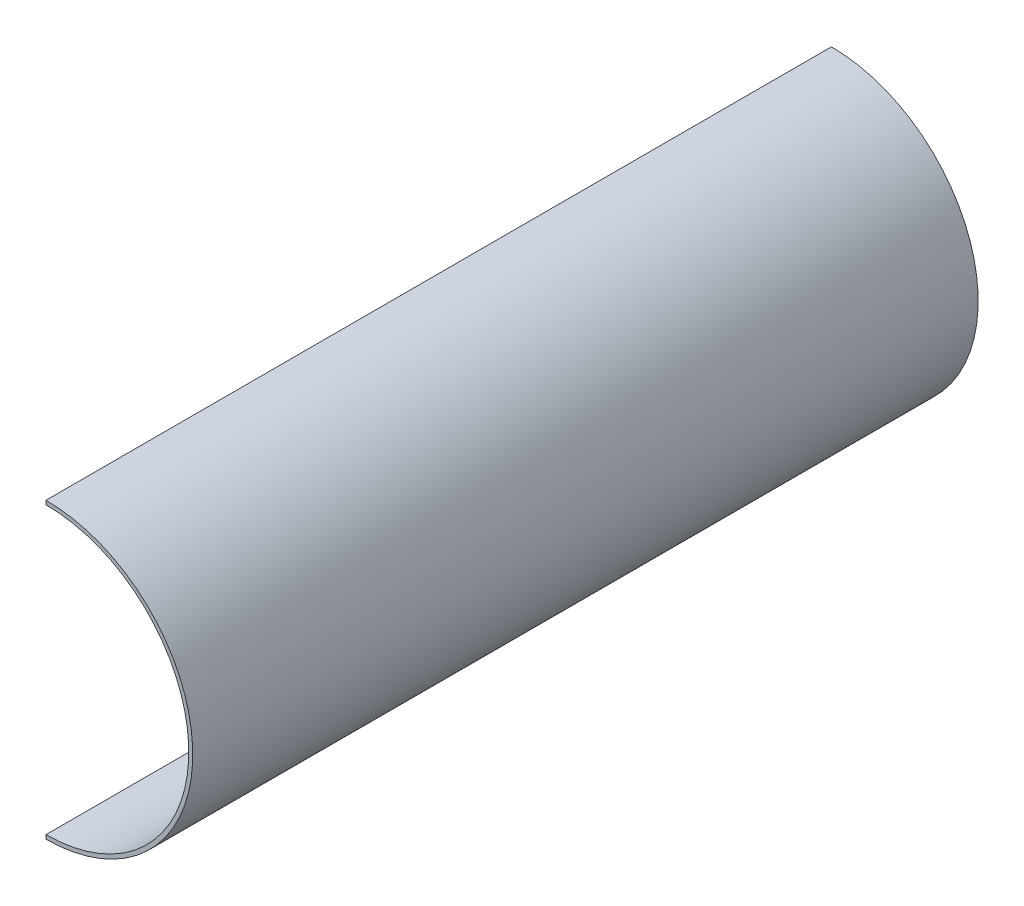
SolidWorks part; units mm, degrees
ref_plane "Front Plane" through (0, 0, 0) normal (0, 0, 1) x (1, 0, 0)
ref_plane "Top Plane" through (0, 0, 0) normal (0, 1, 0) x (1, 0, 0)
ref_plane "Right Plane" through (0, 0, 0) normal (1, 0, 0) x (0, 0, -1)
sketch "Sketch1" plane through (0, 0, 0) normal (0, 0, 1) x (1, 0, 0)
  circle A0 centre (0, 0) radius 18.5
  dimension "D1" = 37
extrude "Boss-Extrude1" add sketch "Sketch1" along normal blind 99
sketch "Sketch2" plane through (0, 0, 99) normal (0, 0, 1) x (1, 0, 0)
  line L0 (0, 18.5) -> (0, 18)
  line L1 (0, -18) -> (0, -18.5)
  arc A0 (0, 18.5) -> (0, -18.5) centre (0, 0) ccw
  arc A1 (0, -18) -> (0, 18) centre (0, 0) ccw
  dimension "D1" = 36
extrude "Cut-Extrude1" cut sketch "Sketch2" against normal blind 99
